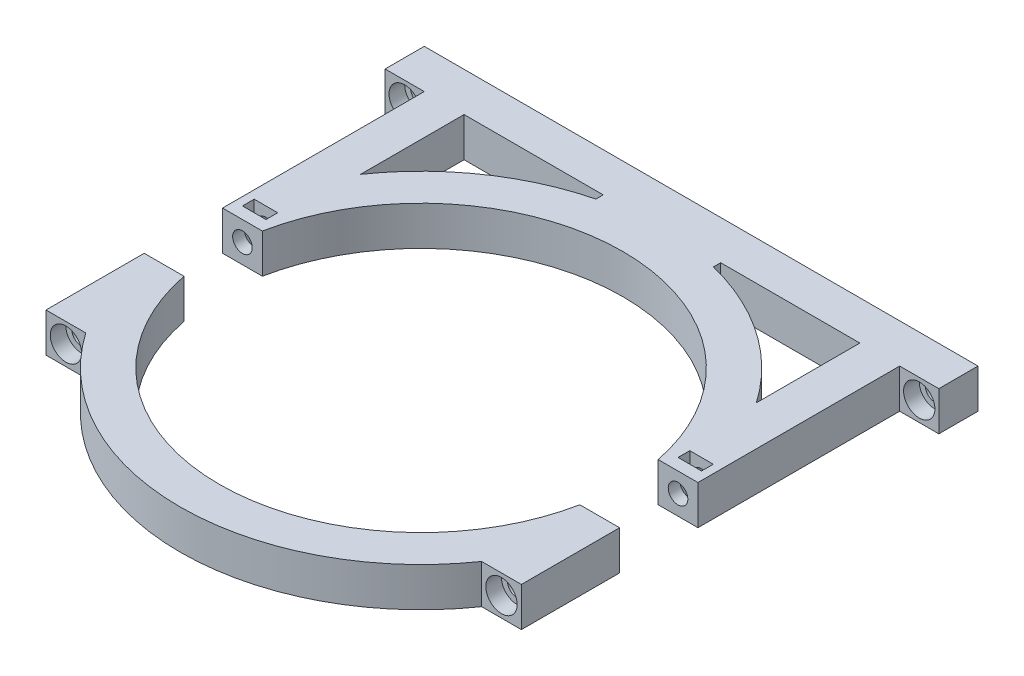
SolidWorks part; units mm, degrees
ref_plane "Front Plane" through (0, 0, 0) normal (0, 0, 1) x (1, 0, 0)
ref_plane "Top Plane" through (0, 0, 0) normal (0, 1, 0) x (1, 0, 0)
ref_plane "Right Plane" through (0, 0, 0) normal (1, 0, 0) x (0, 0, -1)
sketch "Sketch1" plane through (0, 0, 0) normal (0, 1, 0) x (1, 0, 0)
  line L0 (-75.2335, 0) -> (89.0166, 0) construction
  line L1 (-60.6815, 10) -> (-50.5198, 10)
  line L2 (60.6815, -10) -> (50.5198, -10)
  line L3 (50.5198, 10) -> (60.6815, 10)
  line L4 (-50.5198, -10) -> (-60.6815, -10)
  line L5 (-70.6815, 61.5) -> (-60.6815, 61.5)
  line L6 (60.6815, 10) -> (60.6815, 61.5)
  line L7 (-60.6815, 10) -> (-60.6815, 61.5)
  line L8 (70.6815, 61.5) -> (70.6815, 71.5)
  line L9 (70.6815, 71.5) -> (-70.6815, 71.5)
  line L10 (-70.6815, 71.5) -> (-70.6815, 61.5)
  line L11 (60.6815, 61.5) -> (70.6815, 61.5)
  line L12 (15, 61.5) -> (50.5198, 61.5)
  line L13 (50.5198, 61.5) -> (50.5198, 35.0714)
  line L14 (-60.6815, -35.0714) -> (-60.6815, -10)
  line L15 (60.6815, -10) -> (60.6815, -35.0714)
  line L16 (-15, 61.5) -> (-50.5198, 61.5)
  line L17 (-50.5198, 61.5) -> (-50.5198, 35.0714)
  line L18 (50.5198, -35.0714) -> (60.6815, -35.0714)
  line L19 (-50.5198, -35.0714) -> (-60.6815, -35.0714)
  line L21 (-15, 61.5) -> (-15, 59.6427)
  line L22 (15, 61.5) -> (15, 59.6427)
  arc A0 (-50.5198, -35.0714) -> (50.5198, -35.0714) centre (0, 0) ccw
  arc A1 (-50.5198, -10) -> (50.5198, -10) centre (0, 0) ccw
  arc A2 (50.5198, 10) -> (-50.5198, 10) centre (0, 0) ccw
  arc A4 (50.5198, 35.0714) -> (15, 59.6427) centre (0, 0) ccw
  arc A5 (-50.5198, -35.0714) -> (50.5198, -35.0714) centre (0, 0) ccw
  arc A6 (-15, 59.6427) -> (-50.5198, 35.0714) centre (0, 0) ccw
  dimension "D1" = 103
  dimension "D2" = 10
  dimension "D3" = 10
  dimension "D4" = 10
  dimension "D5" = 10
  dimension "D6" = 10
  dimension "D7" = 10
extrude "Boss-Extrude1" add sketch "Sketch1" along normal blind 10 contours A2 L3 L6 L11 L8 L9 L10 L5 L7 L1 L13 A4 L22 L12 L21 A6 L17 L16 | A1 L4 L14 L19 A0 L18 L15 L2
sketch "Sketch2" plane through (0, 0, -61.5) normal (0, 0, 1) x (1, 0, 0)
  circle A0 centre (-65.6815, 5) radius 2.5
  circle A1 centre (65.6815, 5) radius 2.5
  dimension "D1" = 5
  dimension "D2" = 5
extrude "Cut-Extrude1" cut sketch "Sketch2" against normal blind 10
sketch "Sketch3" plane through (0, 0, -61.5) normal (0, 0, 1) x (1, 0, 0)
  circle A0 centre (-65.6815, 5) radius 4
  circle A1 centre (65.6815, 5) radius 4
  dimension "D1" = 8
  dimension "D2" = 8
extrude "Cut-Extrude2" cut sketch "Sketch3" against normal blind 4
sketch "Sketch4" plane through (0, 0, 35.0714) normal (0, 0, 1) x (1, 0, 0)
  circle A0 centre (-55.6007, 5) radius 2.5
  dimension "D1" = 5
extrude "Cut-Extrude3" cut sketch "Sketch4" against normal blind 70
sketch "Sketch5" plane through (0, 0, 35.0714) normal (0, 0, 1) x (1, 0, 0)
  circle A0 centre (-55.6007, 5) radius 4
  dimension "D1" = 8
extrude "Cut-Extrude4" cut sketch "Sketch5" against normal blind 4
sketch "Sketch6" plane through (0, 10, 0) normal (0, 1, 0) x (1, 0, 0)
  line L0 (-55.6007, 10) -> (-55.6007, 25.3835) construction
  line L1 (-60.6815, 10) -> (-50.5198, 10) construction
  line L3 (-58.6007, 13) -> (-52.6007, 13)
  line L4 (-58.6007, 13) -> (-58.6007, 16)
  line L5 (-58.6007, 16) -> (-52.6007, 16)
  line L6 (-52.6007, 13) -> (-52.6007, 16)
  line L7 (-58.6007, 13) -> (-52.6007, 16) construction
  line L8 (-58.6007, 16) -> (-52.6007, 13) construction
  point P4 (-55.6007, 14.5)
  dimension "D1" = 3
  dimension "D2" = 6
  dimension "D3" = 3
extrude "Cut-Extrude5" cut sketch "Sketch6" against normal up to next
sketch "Sketch7" plane through (0, 0, 35.0714) normal (0, 0, 1) x (1, 0, 0)
  circle A0 centre (55.6007, 5) radius 2.5
  dimension "D1" = 5
extrude "Cut-Extrude6" cut sketch "Sketch7" against normal blind 70
sketch "Sketch8" plane through (0, 0, 35.0714) normal (0, 0, 1) x (1, 0, 0)
  circle A0 centre (55.6007, 5) radius 4
  dimension "D1" = 8
extrude "Cut-Extrude7" cut sketch "Sketch8" against normal blind 4
sketch "Sketch9" plane through (0, 10, 0) normal (0, 1, 0) x (1, 0, 0)
  line L0 (55.6007, 10) -> (55.6007, 28.1196) construction
  line L1 (50.5198, 10) -> (60.6815, 10) construction
sketch "Sketch11" plane through (0, 10, 0) normal (0, 1, 0) x (1, 0, 0)
  line L0 (55.6007, 10) -> (55.6007, 28.1196) construction
  line L1 (52.6007, 13) -> (58.6007, 13)
  line L2 (52.6007, 13) -> (52.6007, 16)
  line L3 (52.6007, 16) -> (58.6007, 16)
  line L4 (58.6007, 13) -> (58.6007, 16)
  line L5 (52.6007, 13) -> (58.6007, 16) construction
  line L6 (52.6007, 16) -> (58.6007, 13) construction
  line L7 (50.5198, 10) -> (60.6815, 10) construction
  point P0 (55.6007, 14.5)
  dimension "D1" = 3
  dimension "D2" = 3
  dimension "D3" = 6
extrude "Cut-Extrude8" cut sketch "Sketch11" against normal up to next
